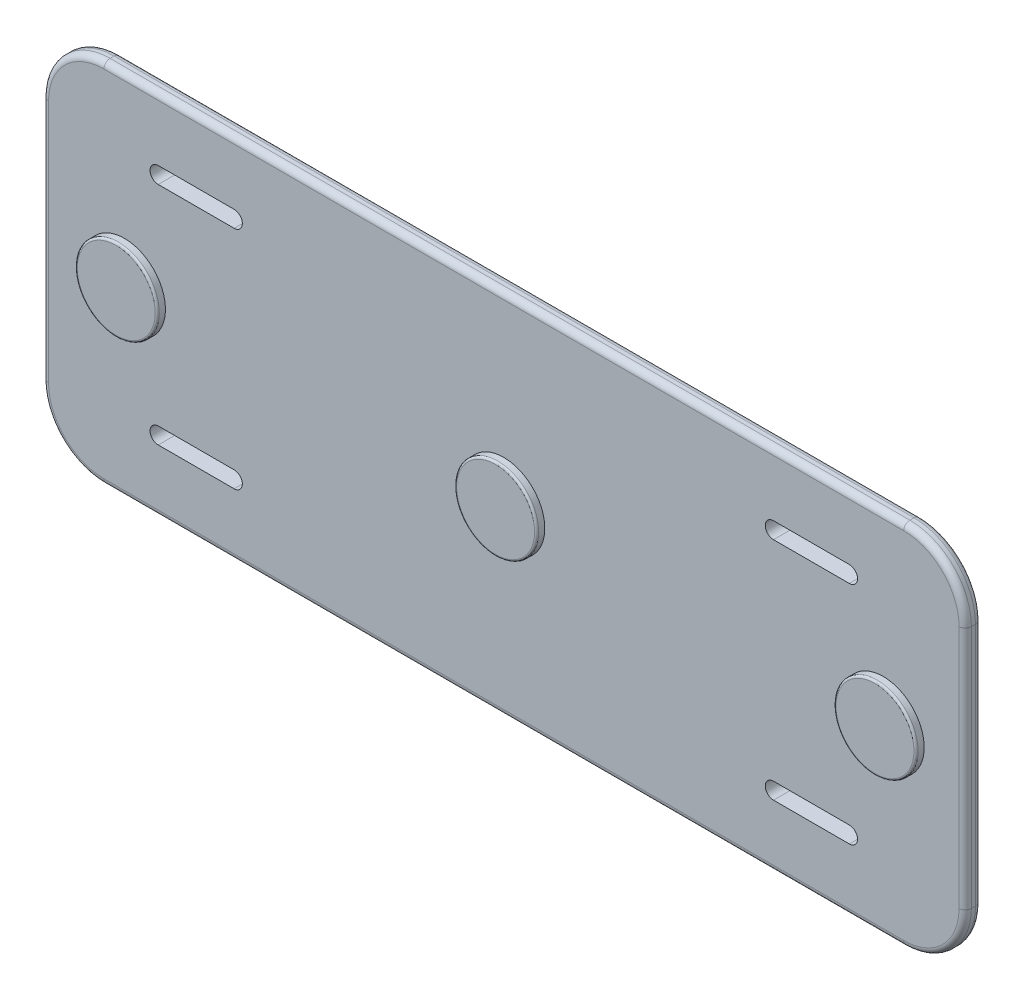
SolidWorks part; units mm, degrees
ref_plane "Front Plane" through (0, 0, 0) normal (0, 0, 1) x (1, 0, 0)
ref_plane "Top Plane" through (0, 0, 0) normal (0, 1, 0) x (1, 0, 0)
ref_plane "Right Plane" through (0, 0, 0) normal (1, 0, 0) x (0, 0, -1)
sketch "Sketch1" plane through (0, 0, 0) normal (0, 0, 1) x (1, 0, 0)
  line L1 (195, 89.5) -> (-195, 89.5)
  line L2 (225, 59.5) -> (225, -59.5)
  line L3 (195, -89.5) -> (-195, -89.5)
  line L4 (-225, 59.5) -> (-225, -59.5)
  line L5 (225, 89.5) -> (-225, -89.5) construction
  line L6 (225, -89.5) -> (-225, 89.5) construction
  arc A0 (-195, -89.5) -> (-225, -59.5) centre (-195, -59.5) cw
  arc A1 (195, -89.5) -> (225, -59.5) centre (195, -59.5) ccw
  arc A2 (225, 59.5) -> (195, 89.5) centre (195, 59.5) ccw
  arc A3 (-195, 89.5) -> (-225, 59.5) centre (-195, 59.5) ccw
  point P0 (0, 0)
  dimension "D3" = 30
  dimension "D1" = 450
  dimension "D2" = 179
extrude "Boss-Extrude1" add sketch "Sketch1" along normal mid plane 8
sketch "Sketch2" plane through (0, 0, 4) normal (0, 0, 1) x (1, 0, 0)
  circle A0 centre (-185, 0) radius 20
  circle A1 centre (185, 0) radius 20
  point P7 (0, 0)
  dimension "D1" = 40
  dimension "D2" = 40
extrude "Boss-Extrude2" add sketch "Sketch2" along normal mid plane 8 contours A1 | A0
sketch "Sketch3" plane through (0, 0, 4) normal (0, 0, 1) x (1, 0, 0)
  circle A0 centre (0, 0) radius 20
  dimension "D1" = 40
extrude "Boss-Extrude3" add sketch "Sketch3" along normal mid plane 8
sketch "Sketch4" plane through (0, 0, 4) normal (0, 0, 1) x (1, 0, 0)
  line L0 (-168.5, 55) -> (-131.5, 55) construction
  line L1 (-168.5, 59) -> (-131.5, 59)
  line L2 (-168.5, 51) -> (-131.5, 51)
  line L3 (0, 0) -> (0, 73.4262) construction
  line L4 (0, 73.4262) -> (0, -74.6925) construction
  line L5 (0, 0) -> (-117.0935, 0) construction
  line L6 (-117.0935, 0) -> (125.7153, 0) construction
  line L7 (168.5, 55) -> (131.5, 55) construction
  line L8 (168.5, 59) -> (131.5, 59)
  line L9 (168.5, 51) -> (131.5, 51)
  line L10 (-168.5, -55) -> (-131.5, -55) construction
  line L11 (-168.5, -59) -> (-131.5, -59)
  line L12 (-168.5, -51) -> (-131.5, -51)
  line L13 (168.5, -55) -> (131.5, -55) construction
  line L14 (168.5, -59) -> (131.5, -59)
  line L15 (168.5, -51) -> (131.5, -51)
  arc A0 (-168.5, 59) -> (-168.5, 51) centre (-168.5, 55) ccw
  arc A1 (-131.5, 51) -> (-131.5, 59) centre (-131.5, 55) ccw
  arc A2 (168.5, 59) -> (168.5, 51) centre (168.5, 55) cw
  arc A3 (131.5, 51) -> (131.5, 59) centre (131.5, 55) cw
  arc A4 (-168.5, -59) -> (-168.5, -51) centre (-168.5, -55) cw
  arc A5 (-131.5, -51) -> (-131.5, -59) centre (-131.5, -55) cw
  arc A6 (168.5, -59) -> (168.5, -51) centre (168.5, -55) ccw
  arc A7 (131.5, -51) -> (131.5, -59) centre (131.5, -55) ccw
  point P2 (-150, 55)
  point P15 (150, 55)
  point P22 (-150, -55)
  point P29 (150, -55)
  point P34 (0, 0)
  point P35 (0, 0)
  point P36 (0, 0)
  dimension "D1" = 4
  dimension "D2" = 37
  dimension "D3" = 150
  dimension "D4" = 55
extrude "Cut-Extrude2" cut sketch "Sketch4" against normal blind 8
fillet "Fillet1" radius 3 16 edges at (216.2132, 80.7132, -4) (225, 0, -4) (216.2132, -80.7132, -4) (0, -89.5, -4) (-216.2132, -80.7132, -4) (-225, 0, -4) (-216.2132, 80.7132, -4) (216.2132, 80.7132, 4) (225, 0, 4) (216.2132, -80.7132, 4) (0, -89.5, 4) (-216.2132, -80.7132, 4) (-225, 0, 4) (-216.2132, 80.7132, 4) (0, 89.5, -4) (0, 89.5, 4)
fillet "Fillet2" radius 1 3 edges at (205, 0, 8) (20, 0, 8) (-165, 0, 8)
